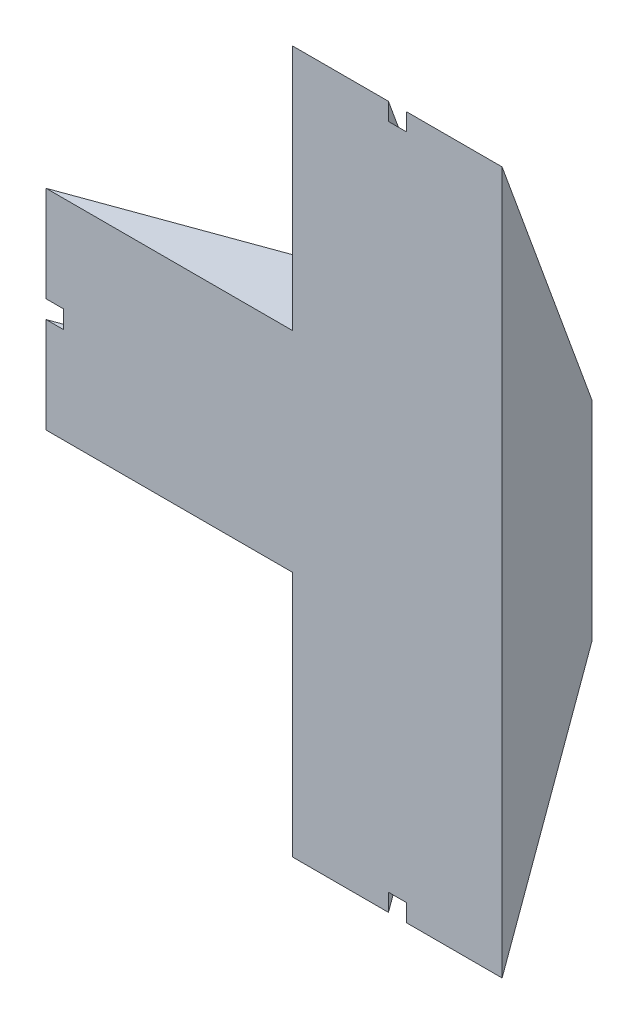
SolidWorks part; units mm, degrees
ref_plane "Front Plane" through (0, 0, 0) normal (0, 0, 1) x (1, 0, 0)
ref_plane "Top Plane" through (0, 0, 0) normal (0, 1, 0) x (1, 0, 0)
ref_plane "Right Plane" through (0, 0, 0) normal (1, 0, 0) x (0, 0, -1)
sketch "Sketch1" plane through (0, 0, 0) normal (0, 1, 0) x (1, 0, 0)
  line L0 (0, 0) -> (412.1216, 0)
  line L1 (412.1216, 0) -> (412.1216, 150)
  line L2 (412.1216, 150) -> (0, 0)
  dimension "D1" = 150
  dimension "D2" = 20
extrude "Boss-Extrude1" add sketch "Sketch1" along normal blind 350
sketch "Sketch2" plane through (412.1216, 0, 0) normal (1, 0, 0) x (0, 0, -1)
  line L4 (0, 0) -> (150, 0)
  line L5 (150, 0) -> (150, 350)
  line L6 (150, 350) -> (0, 350)
  line L7 (0, 350) -> (0, 0)
  line L8 (0, 0) -> (150, 0)
  line L9 (150, 0) -> (150, 350)
  line L10 (150, 350) -> (0, 350)
  line L11 (0, 350) -> (0, 0)
  dimension "D1" = 0
extrude "Boss-Extrude2" add sketch "Sketch2" along normal blind 350
sketch "Sketch4" plane through (762.1216, 0, 0) normal (1, 0, 0) x (0, 0, -1)
  line L0 (0, 350) -> (0, 762.1216)
  line L1 (0, 762.1216) -> (150, 350)
  line L2 (0, 350) -> (150, 350)
  line L6 (0, 350) -> (0, 0)
  line L7 (0, 0) -> (150, 0)
  line L8 (150, 0) -> (150, 350)
  line L9 (150, 350) -> (0, 350)
  line L10 (0, 350) -> (0, 0)
  line L11 (0, 0) -> (150, 0)
  line L12 (150, 0) -> (150, 350)
  line M10 (150, 350) -> (0, 350)
  dimension "D1" = 20
  dimension "D2" = 0
extrude "Boss-Extrude3" add sketch "Sketch4" against normal blind 350 contours L1 L0 M10
sketch "Sketch5" plane through (762.1216, 0, 0) normal (1, 0, 0) x (0, 0, -1)
  line L0 (0, 0) -> (0, -412.1216)
  line L1 (0, -412.1216) -> (150, 0)
  line L2 (0, 0) -> (150, 0)
  dimension "D1" = 20
extrude "Boss-Extrude4" add sketch "Sketch5" against normal blind 350
sketch "Sketch6" plane through (0, 0, 0) normal (-0.342, 0, -0.9397) x (-0.9397, 0, 0.342)
  line L0 (0, 160) -> (-438.5707, 160)
  line L1 (0, 350) -> (0, 0) construction
  line L2 (-438.5707, 350) -> (-438.5707, 0) construction
  line L3 (0, 175) -> (-124.4564, 175) construction
  line L4 (0, 190) -> (-438.5707, 190)
  line L5 (0, 190) -> (0, 160)
  line L6 (-438.5707, 190) -> (-438.5707, 160)
  dimension "D1" = 15
extrude "Cut-Extrude1" cut sketch "Sketch6" against normal blind 10
sketch "Sketch7" plane through (0, 0, -150) normal (0, 0, -1) x (-1, 0, 0)
  line L0 (-587.1216, 350) -> (-587.1216, 0) construction
  line L1 (-762.1216, 350) -> (-412.1216, 350) construction
  line L2 (-762.1216, 0) -> (-412.1216, 0) construction
  line L3 (-415.5418, 175) -> (-762.1216, 175) construction
  line L4 (-415.5418, 190) -> (-415.5418, 160) construction
  line L5 (-762.1216, 0) -> (-762.1216, 350) construction
  line L6 (-412.1216, 190) -> (-572.1216, 190)
  line L7 (-572.1216, 190) -> (-572.1216, 350)
  line L8 (-412.1216, 160) -> (-572.1216, 160)
  line L9 (-572.1216, 160) -> (-572.1216, 0)
  line L10 (-602.1216, 160) -> (-602.1216, 0)
  line L11 (-602.1216, 190) -> (-602.1216, 350)
  line L12 (-602.1216, 190) -> (-602.1216, 164.9009)
  line L13 (-602.1216, 0) -> (-572.1216, 0)
  line L14 (-602.1216, 350) -> (-572.1216, 350)
  line L15 (-412.1216, 160) -> (-412.1216, 190)
  line L16 (-602.1216, 164.9009) -> (-602.1216, 160)
  dimension "D1" = 15
extrude "Cut-Extrude2" cut sketch "Sketch7" against normal blind 10
sketch "Sketch8" plane through (0, -48.2091, -132.4533) normal (0, -0.342, -0.9397) x (-1, 0, 0)
  line L0 (-602.1216, 51.303) -> (-602.1216, -387.2676)
  line L1 (-412.1216, -387.2676) -> (-762.1216, -387.2676) construction
  line L2 (-572.1216, 51.303) -> (-572.1216, -387.2676)
  line L3 (-572.1216, -387.2676) -> (-602.1216, -387.2676)
  line L4 (-602.1216, 51.303) -> (-572.1216, 51.303)
extrude "Cut-Extrude3" cut sketch "Sketch8" against normal blind 10
sketch "Sketch9" plane through (0, 89.1513, -244.9412) normal (0, 0.342, -0.9397) x (-1, 0, 0)
  line L0 (-602.1216, 277.5894) -> (-602.1216, 716.1601)
  line L1 (-412.1216, 716.1601) -> (-762.1216, 716.1601) construction
  line L2 (-572.1216, 277.5894) -> (-572.1216, 716.1601)
  line L3 (-572.1216, 716.1601) -> (-602.1216, 716.1601)
  line L4 (-602.1216, 277.5894) -> (-572.1216, 277.5894)
extrude "Cut-Extrude4" cut sketch "Sketch9" against normal blind 10
